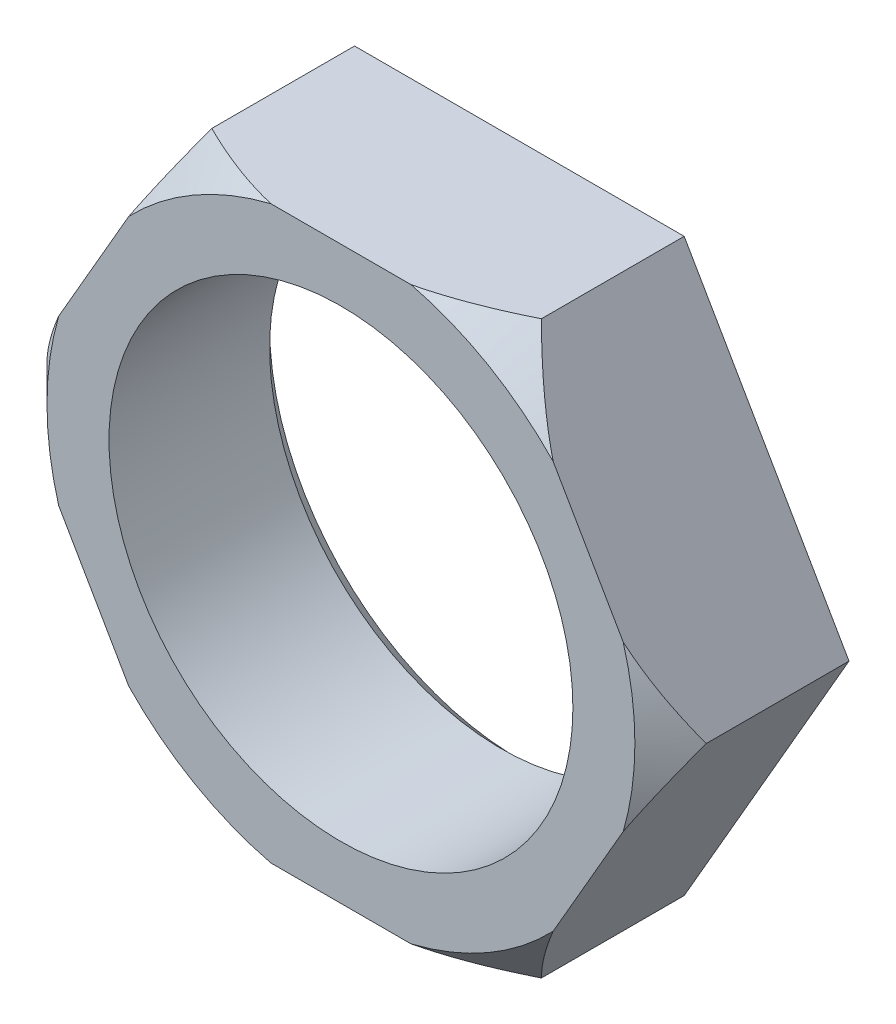
SolidWorks part; units mm, degrees
ref_plane "Płaszczyzna przednia" through (0, 0, 0) normal (0, 0, 1) x (1, 0, 0)
ref_plane "Płaszczyzna górna" through (0, 0, 0) normal (0, 1, 0) x (1, 0, 0)
ref_plane "Płaszczyzna prawa" through (0, 0, 0) normal (1, 0, 0) x (0, 0, -1)
sketch "Szkic1" plane through (0, 0, 0) normal (0, 0, 1) x (1, 0, 0)
  line L1 (9.2376, 0) -> (4.6188, 8)
  line L2 (4.6188, 8) -> (-4.6188, 8)
  line L3 (-4.6188, 8) -> (-9.2376, 0)
  line L4 (-9.2376, 0) -> (-4.6188, -8)
  line L5 (-4.6188, -8) -> (4.6188, -8)
  line L6 (4.6188, -8) -> (9.2376, 0)
  circle A0 centre (0, 0) radius 6.5
  dimension "D1" = 13
  dimension "D2" = 16
extrude "Dodanie-wyciągnięcie3" add sketch "Szkic1" along normal blind 5
cosmetic thread "Oznaczenie gwintu1" parameters "D2"=14
sketch "Szkic2" plane through (0, 0, 0) normal (0, 1, 0) x (1, 0, 0)
  line L5 (0, 0) -> (0, -5) construction
  line L6 (4.6188, -5) -> (-4.6188, -5) construction
  line L7 (9.2376, -5) -> (9.2376, -4)
  line L8 (9.2376, -5) -> (9.2376, 0) construction
  line L9 (9.2376, -4) -> (8.2376, -5)
  line L10 (9.2376, -5) -> (4.6188, -5) construction
  line L11 (8.2376, -5) -> (9.2376, -5)
  dimension "D1" = 1
  dimension "D2" = 1
  dimension "D3" = 45
revolve "Wycięcie-obrót3" cut sketch "Szkic2" angle 360 about L5
chamfer "Sfazowanie3" distance 0.5 angle 45 1 edges at (6.5, 0, 0)
